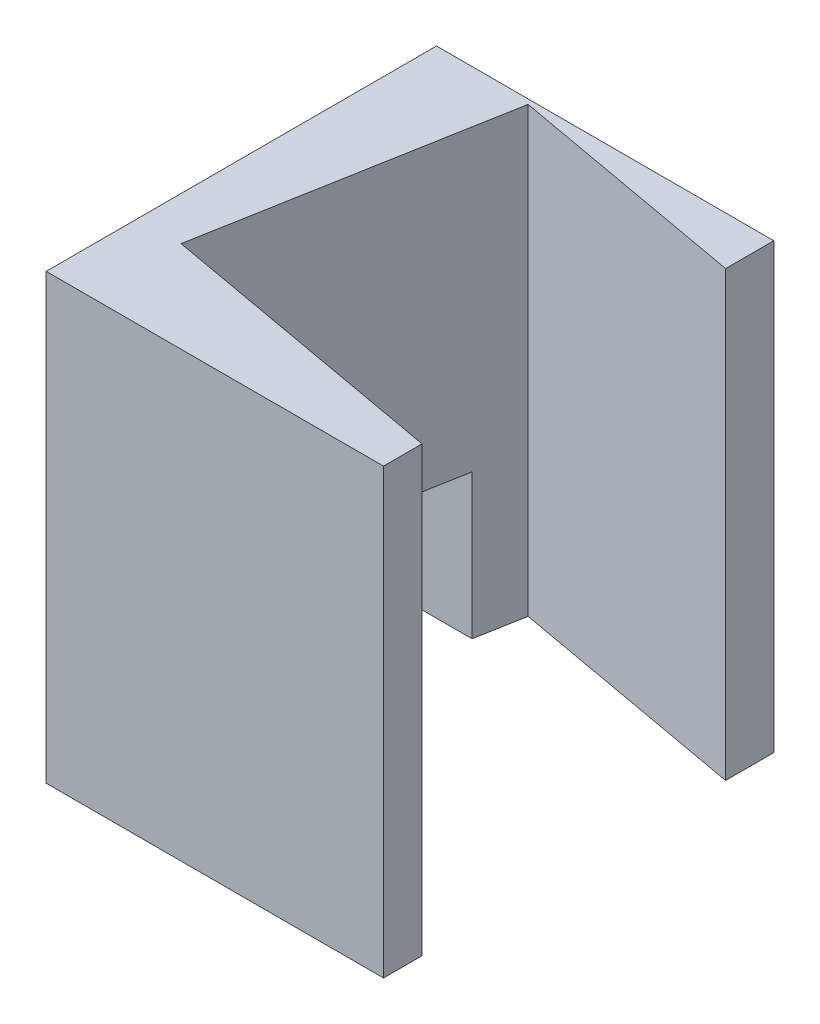
SolidWorks part; units mm, degrees
other "Marca1"
sketch "Croquis16" plane through (-4, 0, 16.4123) normal (-0.1839, 0.8762, 0.4455) x (-0.9734, -0.0995, -0.2061)
ref_plane "Front Plane" through (0, 0, 0) normal (1, 0, 0) x (0, 1, 0)
ref_plane "Top Plane" through (0, 0, 0) normal (0, 0, 1) x (0, 1, 0)
ref_plane "Right Plane" through (0, 0, 0) normal (0, 1, 0) x (-1, 0, 0)
sketch "Croquis17" plane through (0, 0, 0) normal (0, 1, 0) x (-1, 0, 0)
  line L0 (0, 0) -> (-10, 1.8)
  line L1 (-10, 1.8) -> (-10, -0.2)
  line L2 (-10, -0.2) -> (4, -0.2)
  line L3 (4, -0.2) -> (4, 15.9993)
  line L5 (0, 0) -> (2.1967, 12.2039)
  line L6 (2.1967, 12.2039) -> (-10, 14.3993)
  line L7 (-10, 14.3993) -> (-10, 15.9993)
  line L8 (-10, 15.9993) -> (4, 15.9993)
  dimension "D1" = 10
  dimension "D2" = 14
  dimension "D3" = 1.8
  dimension "D4" = 0.2
  dimension "D5" = 1.6
  dimension "D6" = 12.4
extrude "BASE" add sketch "Croquis17" against normal blind 18.4
sketch "Croquis19" plane through (0, 0, 0) normal (0.9842, 0, 0.1772) x (0, 1, 0)
  line L0 (-18.4, 12.4) -> (-18.4, 0) construction
  line L1 (-18.4, 10.4) -> (-12.4, 10.4)
  line L2 (-18.4, 10.4) -> (-18.4, 2)
  line L3 (-18.4, 2) -> (-12.4, 2)
  line L4 (-12.4, 10.4) -> (-12.4, 2)
  line L5 (-18.4, 12.4) -> (0, 12.4) construction
  point P6 (-18.4, 6.2)
  dimension "D1" = 6
  dimension "D2" = 2
sketch "Croquis20" plane through (-4, 0, 0) normal (-1, 0, 0) x (0, -1, 0)
  line L0 (18.4, 1.9684) -> (12.4, 1.9684) construction
  line L1 (18.4, 10.2355) -> (18.4, 1.9684) construction
  line L2 (18.4, 10.2355) -> (12.4, 10.2355) construction
  line L3 (12.4, 10.2355) -> (12.4, 1.9684) construction
  line L4 (18.4, 1.9684) -> (12.4, 1.9684)
  line L5 (18.4, 10.2355) -> (18.4, 1.9684)
  line L6 (18.4, 10.2355) -> (12.4, 10.2355)
  line L7 (12.4, 10.2355) -> (12.4, 1.9684)
loft "WIRE_WINDOW" cut profiles "Croquis19", "Croquis20"
